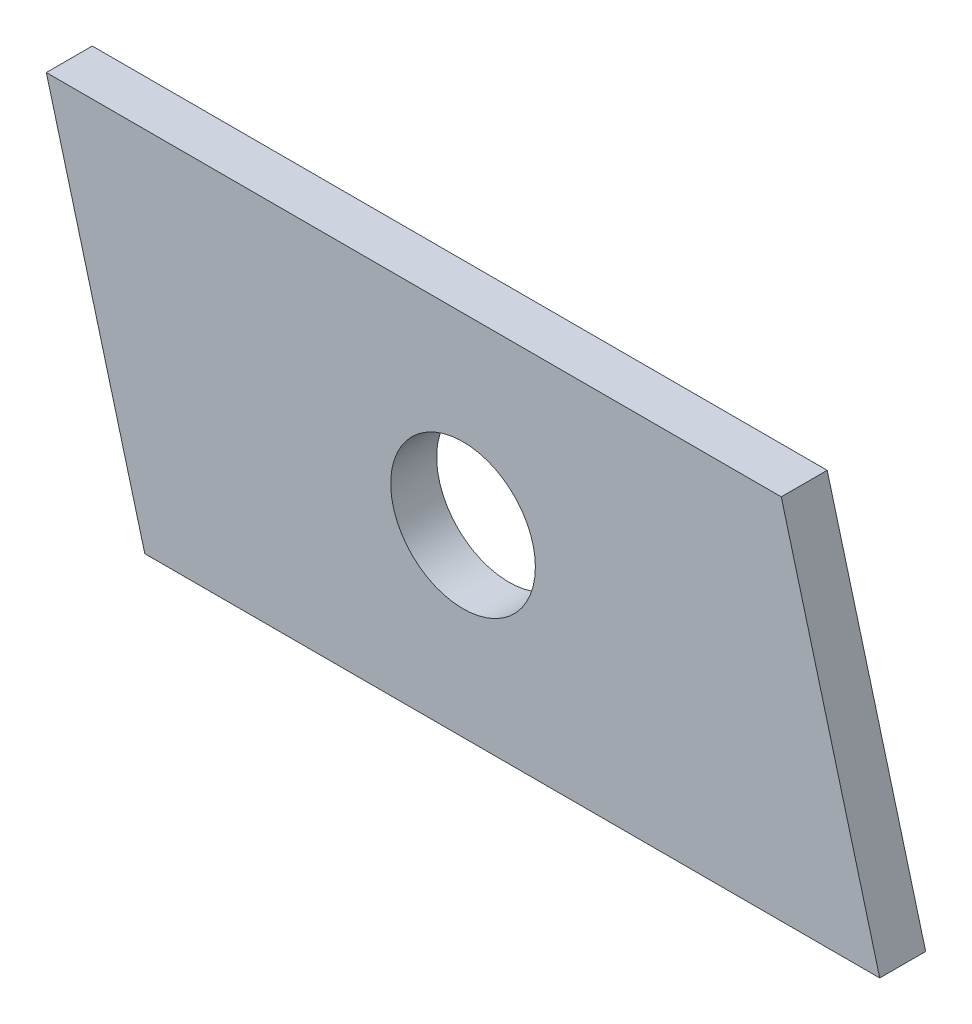
SolidWorks part; units mm, degrees
material "Plain Carbon Steel"
ref_plane "Front Plane" through (0, 0, 0) normal (0, 0, 1) x (1, 0, 0)
ref_plane "Top Plane" through (0, 0, 0) normal (0, 1, 0) x (1, 0, 0)
ref_plane "Right Plane" through (0, 0, 0) normal (1, 0, 0) x (0, 0, -1)
sketch "Sketch1" plane through (0, 0, 0) normal (0, 0, 1) x (1, 0, 0)
  line L0 (-218.7069, 117.1731) -> (-211.901, 91.7731)
  line L1 (-211.901, 91.7731) -> (-161.101, 91.7731)
  line L3 (-167.9069, 117.1731) -> (-218.7069, 117.1731)
  line L8 (-215.304, 104.4731) -> (-164.504, 104.4731) construction
  line L12 (-167.9069, 117.1731) -> (-161.101, 91.7731)
  circle A0 centre (-189.904, 104.4731) radius 5
  dimension "D2" = 10
  dimension "D1" = 25.4
  dimension "D3" = 50.8
  dimension "D4" = 75
extrude "Boss-Extrude1" add sketch "Sketch1" against normal blind 3.175
